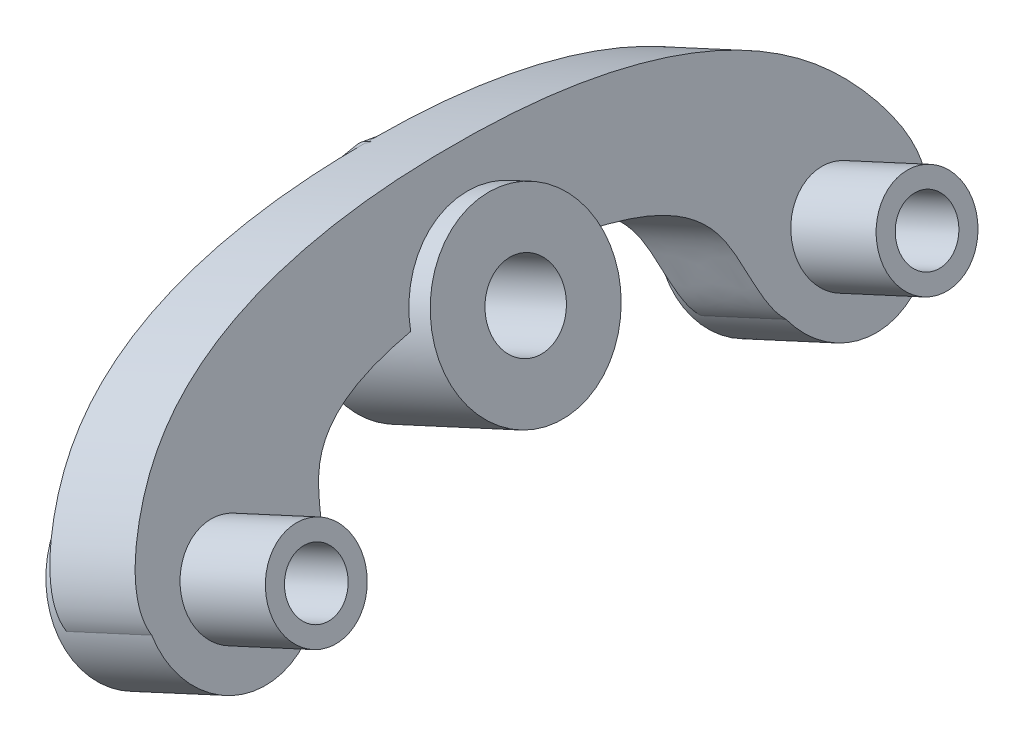
SolidWorks part; units mm, degrees
material "Aleación 6061"
ref_plane "Alzado" through (0, 0, 0) normal (0, 0, 1) x (1, 0, 0)
ref_plane "Planta" through (0, 0, 0) normal (0, 1, 0) x (1, 0, 0)
ref_plane "Vista lateral" through (0, 0, 0) normal (1, 0, 0) x (0, 0, -1)
sketch3d "Sk_puntos_Plano_puente"
  point P0 (429.5, 386.8, 0)
  point P1 (446.2623, 350.4816, 0)
  point P2 (429.5, 386.8, 40)
ref_plane "Plano_puente" through (501.2483, 231.3454, 0) normal (-0.908, -0.4191, 0) x (0, 0, 1)
sketch "Sk_Arco" plane through (501.2483, 231.3454, 0) normal (-0.908, -0.4191, 0) x (0, 0, 1)
  spline S0 degree 3 poles (-18.2045, 160.2191) (-36.14, 164.3802) (-30.9281, 175.4838) (-23.7009, 181.126) (-12.5145, 184.2504) (0, 184.9587) (12.5145, 184.2504) (23.7009, 181.126) (30.9281, 175.4838) (36.14, 164.3802) (18.2045, 160.2191) (18.3333, 172.4724) (9.189, 175.8899) (0, 176.3926) (-9.189, 175.8899) (-18.3333, 172.4724) (-18.2045, 160.2191) (-36.14, 164.3802) (-30.9281, 175.4838) knots -0.181031 -0.130737 -0.083228 0 0.045415 0.102929 0.174939 0.256275 0.337612 0.409622 0.467136 0.512551 0.595779 0.643288 0.693582 0.756275 0.818969 0.869263 0.916772 1 1.045415 1.102929 1.174939 only from (-33, 167.2132) to (-33, 167.2132)
extrude "Arco" add sketch "Sk_Arco" along normal mid plane 8
sketch3d "Sk_Nervio"
  line L0 (422.0966, 393.2954, -14) -> (421.2585, 395.1113, 0)
  line L1 (421.2585, 395.1113, 0) -> (422.0966, 393.2954, 14)
  dimension "D1" = 14.1421
  dimension "D2" = 14.1421
sweep "Nervio" add path "Sk_Nervio" circular profile diameter 5 parameters "D3"=5
sketch3d "Sk_Buje_central"
  line L0 (422.7951, 387.0095, 0) -> (433.6906, 392.0382, 0)
  dimension "D1" = 12
sweep "Buje_central" add path "Sk_Buje_central" circular profile diameter 15 parameters "D3"=15
sketch3d "Sk_Buje_pivote_izq"
  line L0 (426.4269, 381.5269, -26) -> (434.5985, 385.2984, -26)
  dimension "D1" = 9
sweep "Buje_pivote_izq" add path "Sk_Buje_pivote_izq" circular profile diameter 14 parameters "D3"=14
sketch3d "Sk_Pivote_izq"
  line L0 (434.5985, 385.2984, -26) -> (441.8622, 388.6508, -26)
  dimension "D1" = 8
sweep "Pivote_izq" add path "Sk_Pivote_izq" circular profile diameter 8 parameters "D3"=8
sketch3d "Sk_Tope_muelle_izq"
  line L0 (425.1697, 391.4096, -16.12) -> (425.1697, 391.4096, -19.12)
  line L1 (425.1697, 391.4096, -19.12) -> (419.722, 388.8953, -19.12)
  dimension "D1" = 3
  dimension "D2" = 6
sweep "Tope_muelle_izq" add path "Sk_Tope_muelle_izq" circular profile diameter 2.5 parameters "D3"=2.5
sketch3d "Sk_Buje_pivote_dcho"
  line L0 (426.4269, 381.5269, 26) -> (434.5985, 385.2984, 26)
  dimension "D1" = 9
sweep "Buje_pivote_dcho" add path "Sk_Buje_pivote_dcho" circular profile diameter 14 parameters "D3"=14
sketch3d "Sk_Pivote_dcho"
  line L0 (434.5985, 385.2984, 26) -> (441.8622, 388.6508, 26)
  dimension "D1" = 8
sweep "Pivote_dcho" add path "Sk_Pivote_dcho" circular profile diameter 8 parameters "D3"=8
sketch3d "Sk_Tope_muelle_dcho"
  line L0 (425.1697, 391.4096, 16.12) -> (425.1697, 391.4096, 19.12)
  line L1 (425.1697, 391.4096, 19.12) -> (419.722, 388.8953, 19.12)
  dimension "D1" = 3
  dimension "D2" = 6
sweep "Tope_muelle_dcho" add path "Sk_Tope_muelle_dcho" circular profile diameter 2.5 parameters "D3"=2.5
sketch3d "Sk_Taladro_central"
  line L0 (420.9792, 386.1714, 0) -> (435.5065, 392.8763, 0)
  dimension "D1" = 16
sweep "Taladro_central" cut path "Sk_Taladro_central" circular profile diameter 6.4 parameters "D3"=6.4
sketch3d "Sk_Rosca_pivote_izq"
  line L0 (425.5189, 381.1078, -26) -> (442.7702, 389.0699, -26)
  dimension "D1" = 19
sweep "Rosca_pivote_izq" cut path "Sk_Rosca_pivote_izq" circular profile diameter 5 parameters "D3"=5
sketch3d "Sk_Rosca_pivote_dcho"
  line L0 (425.5189, 381.1078, 26) -> (442.7702, 389.0699, 26)
  dimension "D1" = 19
sweep "Rosca_pivote_dcho" cut path "Sk_Rosca_pivote_dcho" circular profile diameter 5 parameters "D3"=5
sketch3d "Sk_puntos_Plano_tiro_ref"
  point P0 (429.5, 386.8, 0)
  point P1 (465.8184, 403.5623, 0)
  point P2 (429.5, 386.8, 40)
ref_plane "Plano_tiro_ref" through (-71.7483, 155.4546, 0) normal (0.4191, -0.908, 0) x (-0.908, -0.4191, 0)
